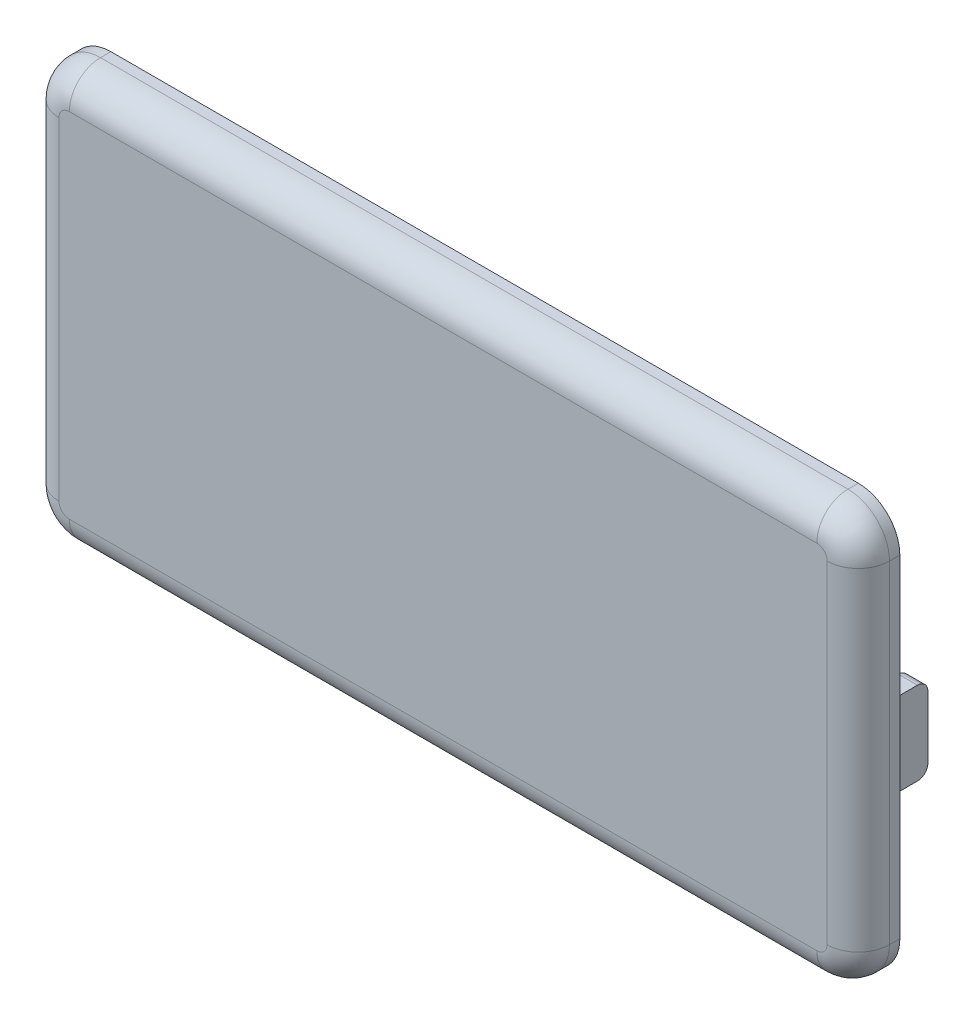
SolidWorks part; units mm, degrees
material "ABS"
ref_plane "Front Plane" through (0, 0, 0) normal (0, 0, 1) x (1, 0, 0)
ref_plane "Top Plane" through (0, 0, 0) normal (0, 1, 0) x (1, 0, 0)
ref_plane "Right Plane" through (0, 0, 0) normal (1, 0, 0) x (0, 0, -1)
sketch "Sketch1" plane through (0, 0, 0) normal (0, 0, 1) x (1, 0, 0)
  line L0 (-40, 0) -> (40, 0) construction
  line L1 (-40, 20) -> (40, 20)
  line L2 (-40, 20) -> (-40, -20)
  line L3 (-40, -20) -> (40, -20)
  line L4 (40, 20) -> (40, -20)
  line L5 (0, 20) -> (0, -20) construction
  dimension "D1" = 40
  dimension "D2" = 80
extrude "Boss-Extrude1" add sketch "Sketch1" along normal blind 4
fillet "Fillet1" radius 4 4 edges at (-40, -20, 2) (40, -20, 2) (40, 20, 2) (-40, 20, 2)
fillet "Fillet2" radius 3 8 edges at (-38.8284, 18.8284, 4) (0, 20, 4) (38.8284, 18.8284, 4) (40, 0, 4) (38.8284, -18.8284, 4) (0, -20, 4) (-38.8284, -18.8284, 4) (-40, 0, 4)
sketch "Sketch2" plane through (0, 0, 0) normal (0, 0, -1) x (-1, 0, 0)
  line L1 (37, -17) -> (-37, -17)
  line L2 (37, -17) -> (37, 17)
  line L3 (37, 17) -> (-37, 17)
  line L4 (-37, -17) -> (-37, 17)
  line L5 (37, -17) -> (-37, 17) construction
  line L6 (37, 17) -> (-37, -17) construction
  point P0 (0, 0)
  dimension "D1" = 74
  dimension "D2" = 34
extrude "Cut-Extrude1" cut sketch "Sketch2" against normal blind 1
sketch "Sketch3" plane through (0, 0, 0) normal (0, 1, 0) x (0, 0, -1)
  line L0 (0, -37) -> (3, -38.0919)
  line L2 (3, -38.0919) -> (3, -39.7)
  line L3 (3, -39.7) -> (0, -39.7)
  line L4 (0, -39.7) -> (0, -37)
  dimension "D1" = 2.7
  dimension "D2" = 3
  dimension "D3" = 110
extrude "Boss-Extrude2" add sketch "Sketch3" along normal mid plane 8
fillet "Fillet3" radius 1 2 edges at (38.896, -4, -3) (38.896, 4, -3)
sketch "Sketch4" plane through (0, 0, 1) normal (0, 0, -1) x (-1, 0, 0)
  line L0 (-20, 3.45) -> (-20, -3.45) construction
  line L1 (-23.45, 0) -> (-16.55, 0) construction
  line L2 (-23.3019, -1) -> (-21, -1)
  line L3 (-21, 3.3019) -> (-21, 1)
  line L4 (-23.3019, 1) -> (-21, 1)
  line L5 (-19, 3.3019) -> (-19, 1)
  line L6 (-21, -1) -> (-21, -3.3019)
  line L7 (-19, -1) -> (-16.6981, -1)
  line L8 (-21, 3.45) -> (-21, -3.45) construction
  line L9 (-19, 1) -> (-16.6981, 1)
  line L10 (-2.3, -1) -> (2.3, -1) construction
  line L11 (-19, -1) -> (-19, -3.3019)
  line L12 (-2.3, 1) -> (2.3, 1) construction
  line L13 (-2.3, 0) -> (2.3, 0) construction
  line L14 (-19, 3.45) -> (-19, -3.45) construction
  line L15 (-20, 0) -> (20, 0) construction
  arc A0 (-23.3019, 1) -> (-23.3019, -1) centre (-20, 0) ccw
  arc A1 (-19, 3.3019) -> (-21, 3.3019) centre (-20, 0) ccw
  arc A2 (-16.6981, -1) -> (-16.6981, 1) centre (-20, 0) ccw
  arc A3 (-21, -3.3019) -> (-19, -3.3019) centre (-20, 0) ccw
  dimension "D1" = 6.9
  dimension "D4" = 40
  dimension "D2" = 1
  dimension "D3" = 1
extrude "Boss-Extrude3" add sketch "Sketch4" along normal blind 9.5
sketch "Sketch5" plane through (0, 0, 0) normal (0, 1, 0) x (0, 0, -1)
  line L0 (-1, -20) -> (8.5, -20) construction
  line L1 (8.5, -21) -> (8.5, -19) construction
  line L2 (5.5, -16.55) -> (8.5, -16.55)
  line L3 (8.5, -16.55) -> (8.5, -17.4985)
  line L6 (5.5, -16.55) -> (8.0868, -17.0061)
  arc A0 (8.0868, -17.0061) -> (8.5, -17.4985) centre (8, -17.4985) cw
  dimension "D1" = 3
  dimension "D2" = 0.5
  dimension "D3" = 10
revolve "Cut-Revolve1" cut sketch "Sketch5" angle 360 about L0
pattern_linear "LPattern1" count 2 spacing 40 along (-1, 0, 0) of "Boss-Extrude3", "Cut-Revolve1"
